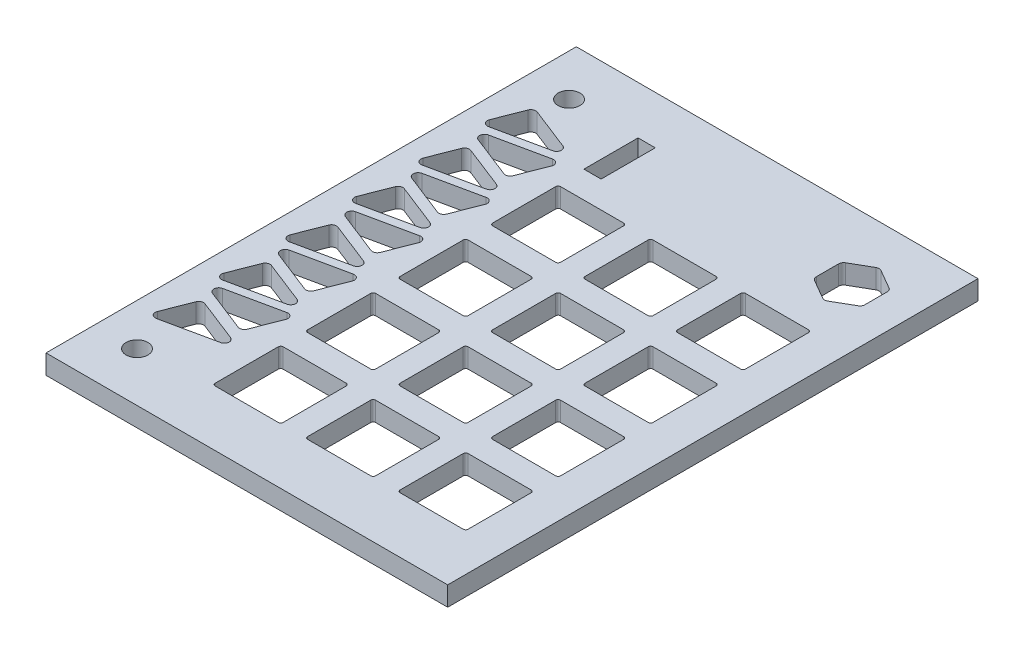
SolidWorks part; units mm, degrees
material "ABS"
ref_plane "Piano frontale" through (0, 0, 0) normal (0, 0, 1) x (1, 0, 0)
ref_plane "Piano superiore" through (0, 0, 0) normal (0, 1, 0) x (1, 0, 0)
ref_plane "Piano destro" through (0, 0, 0) normal (1, 0, 0) x (0, 0, -1)
sketch "Schizzo1" plane through (0, 0, 0) normal (0, 1, 0) x (1, 0, 0)
  line L0 (-41.375, 54.625) -> (41.375, -54.625) construction
  line L1 (-41.375, 54.625) -> (41.375, 54.625)
  line L2 (-41.375, 54.625) -> (-41.375, -54.625)
  line L3 (-41.375, -54.625) -> (41.375, -54.625)
  line L4 (41.375, 54.625) -> (41.375, -54.625)
  line L5 (41.375, 54.625) -> (-41.375, -54.625) construction
  line L6 (-32.75, -44.5) -> (-32.75, 44.5) construction
  line L7 (-32.75, 0) -> (0, 0) construction
  circle A0 centre (-32.75, 44.5) radius 2.25
  circle A1 centre (-32.75, -44.5) radius 2.25
  point P4 (0, 0)
  dimension "D3" = 4.5
  dimension "D1" = 82.75
  dimension "D2" = 109.25
  dimension "D4" = 89
  dimension "D5" = 8.625
extrude "Estrusione-Estrusione1" add sketch "Schizzo1" along normal blind 4
sketch "Schizzo2" plane through (0, 4, 0) normal (0, 1, 0) x (1, 0, 0)
  line L0 (41.375, -54.625) -> (41.375, 54.625) construction
  line L1 (-41.375, -54.625) -> (41.375, -54.625) construction
  line B0 (36.075, -45.625) -> (36.075, 30.575)
  line B1 (-21.075, -45.625) -> (36.075, -45.625)
  line B2 (-18.05, 28.05) -> (-5.05, 28.05)
  line B3 (-18.05, 14.05) -> (-5.05, 14.05)
  line B4 (-18.55, 27.55) -> (-18.55, 14.55)
  line B5 (-4.55, 27.55) -> (-4.55, 14.55)
  line B6 (1, 28.05) -> (14, 28.05)
  line B7 (1, 14.05) -> (14, 14.05)
  line B8 (0.5, 27.55) -> (0.5, 14.55)
  line B9 (14.5, 27.55) -> (14.5, 14.55)
  line B10 (20.05, 28.05) -> (33.05, 28.05)
  line B11 (20.05, 14.05) -> (33.05, 14.05)
  line B12 (19.55, 27.55) -> (19.55, 14.55)
  line B13 (33.55, 27.55) -> (33.55, 14.55)
  line B14 (-18.05, 9) -> (-5.05, 9)
  line B15 (-18.05, -5) -> (-5.05, -5)
  line B16 (-18.55, 8.5) -> (-18.55, -4.5)
  line B17 (-4.55, 8.5) -> (-4.55, -4.5)
  line B18 (1, 9) -> (14, 9)
  line B19 (1, -5) -> (14, -5)
  line B20 (0.5, 8.5) -> (0.5, -4.5)
  line B21 (14.5, 8.5) -> (14.5, -4.5)
  line B22 (20.05, 9) -> (33.05, 9)
  line B23 (20.05, -5) -> (33.05, -5)
  line B24 (19.55, 8.5) -> (19.55, -4.5)
  line B25 (33.55, 8.5) -> (33.55, -4.5)
  line B26 (-18.05, -10.05) -> (-5.05, -10.05)
  line B27 (-18.05, -24.05) -> (-5.05, -24.05)
  line B28 (-18.55, -10.55) -> (-18.55, -23.55)
  line B29 (-4.55, -10.55) -> (-4.55, -23.55)
  line B30 (1, -10.05) -> (14, -10.05)
  line B31 (1, -24.05) -> (14, -24.05)
  line B32 (0.5, -10.55) -> (0.5, -23.55)
  line B33 (14.5, -10.55) -> (14.5, -23.55)
  line B34 (20.05, -10.05) -> (33.05, -10.05)
  line B35 (20.05, -24.05) -> (33.05, -24.05)
  line B36 (19.55, -10.55) -> (19.55, -23.55)
  line B37 (33.55, -10.55) -> (33.55, -23.55)
  line B38 (-18.05, -29.1) -> (-5.05, -29.1)
  line B39 (-18.05, -43.1) -> (-5.05, -43.1)
  line B40 (-18.55, -29.6) -> (-18.55, -42.6)
  line B41 (-4.55, -29.6) -> (-4.55, -42.6)
  line B42 (1, -29.1) -> (14, -29.1)
  line B43 (1, -43.1) -> (14, -43.1)
  line B44 (0.5, -29.6) -> (0.5, -42.6)
  line B45 (14.5, -29.6) -> (14.5, -42.6)
  line B46 (20.05, -29.1) -> (33.05, -29.1)
  line B47 (20.05, -43.1) -> (33.05, -43.1)
  line B48 (19.55, -29.6) -> (19.55, -42.6)
  line B49 (33.55, -29.6) -> (33.55, -42.6)
  line B50 (-21.075, 30.575) -> (36.075, 30.575)
  line B51 (-21.075, -45.625) -> (-21.075, 30.575)
  arc B52 (-18.05, 28.05) -> (-18.55, 27.55) centre (-18.05, 27.55) ccw
  arc B53 (-4.55, 27.55) -> (-5.05, 28.05) centre (-5.05, 27.55) ccw
  arc B54 (-18.55, 14.55) -> (-18.05, 14.05) centre (-18.05, 14.55) ccw
  arc B55 (-5.05, 14.05) -> (-4.55, 14.55) centre (-5.05, 14.55) ccw
  arc B56 (1, 28.05) -> (0.5, 27.55) centre (1, 27.55) ccw
  arc B57 (14.5, 27.55) -> (14, 28.05) centre (14, 27.55) ccw
  arc B58 (0.5, 14.55) -> (1, 14.05) centre (1, 14.55) ccw
  arc B59 (14, 14.05) -> (14.5, 14.55) centre (14, 14.55) ccw
  arc B60 (20.05, 28.05) -> (19.55, 27.55) centre (20.05, 27.55) ccw
  arc B61 (33.55, 27.55) -> (33.05, 28.05) centre (33.05, 27.55) ccw
  arc B62 (19.55, 14.55) -> (20.05, 14.05) centre (20.05, 14.55) ccw
  arc B63 (33.05, 14.05) -> (33.55, 14.55) centre (33.05, 14.55) ccw
  arc B64 (-18.05, 9) -> (-18.55, 8.5) centre (-18.05, 8.5) ccw
  arc B65 (-4.55, 8.5) -> (-5.05, 9) centre (-5.05, 8.5) ccw
  arc B66 (-18.55, -4.5) -> (-18.05, -5) centre (-18.05, -4.5) ccw
  arc B67 (-5.05, -5) -> (-4.55, -4.5) centre (-5.05, -4.5) ccw
  arc B68 (1, 9) -> (0.5, 8.5) centre (1, 8.5) ccw
  arc B69 (14.5, 8.5) -> (14, 9) centre (14, 8.5) ccw
  arc B70 (0.5, -4.5) -> (1, -5) centre (1, -4.5) ccw
  arc B71 (14, -5) -> (14.5, -4.5) centre (14, -4.5) ccw
  arc B72 (20.05, 9) -> (19.55, 8.5) centre (20.05, 8.5) ccw
  arc B73 (33.55, 8.5) -> (33.05, 9) centre (33.05, 8.5) ccw
  arc B74 (19.55, -4.5) -> (20.05, -5) centre (20.05, -4.5) ccw
  arc B75 (33.05, -5) -> (33.55, -4.5) centre (33.05, -4.5) ccw
  arc B76 (-18.05, -10.05) -> (-18.55, -10.55) centre (-18.05, -10.55) ccw
  arc B77 (-4.55, -10.55) -> (-5.05, -10.05) centre (-5.05, -10.55) ccw
  arc B78 (-18.55, -23.55) -> (-18.05, -24.05) centre (-18.05, -23.55) ccw
  arc B79 (-5.05, -24.05) -> (-4.55, -23.55) centre (-5.05, -23.55) ccw
  arc B80 (1, -10.05) -> (0.5, -10.55) centre (1, -10.55) ccw
  arc B81 (14.5, -10.55) -> (14, -10.05) centre (14, -10.55) ccw
  arc B82 (0.5, -23.55) -> (1, -24.05) centre (1, -23.55) ccw
  arc B83 (14, -24.05) -> (14.5, -23.55) centre (14, -23.55) ccw
  arc B84 (20.05, -10.05) -> (19.55, -10.55) centre (20.05, -10.55) ccw
  arc B85 (33.55, -10.55) -> (33.05, -10.05) centre (33.05, -10.55) ccw
  arc B86 (19.55, -23.55) -> (20.05, -24.05) centre (20.05, -23.55) ccw
  arc B87 (33.05, -24.05) -> (33.55, -23.55) centre (33.05, -23.55) ccw
  arc B88 (-18.05, -29.1) -> (-18.55, -29.6) centre (-18.05, -29.6) ccw
  arc B89 (-4.55, -29.6) -> (-5.05, -29.1) centre (-5.05, -29.6) ccw
  arc B90 (-18.55, -42.6) -> (-18.05, -43.1) centre (-18.05, -42.6) ccw
  arc B91 (-5.05, -43.1) -> (-4.55, -42.6) centre (-5.05, -42.6) ccw
  arc B92 (1, -29.1) -> (0.5, -29.6) centre (1, -29.6) ccw
  arc B93 (14.5, -29.6) -> (14, -29.1) centre (14, -29.6) ccw
  arc B94 (0.5, -42.6) -> (1, -43.1) centre (1, -42.6) ccw
  arc B95 (14, -43.1) -> (14.5, -42.6) centre (14, -42.6) ccw
  arc B96 (20.05, -29.1) -> (19.55, -29.6) centre (20.05, -29.6) ccw
  arc B97 (33.55, -29.6) -> (33.05, -29.1) centre (33.05, -29.6) ccw
  arc B98 (19.55, -42.6) -> (20.05, -43.1) centre (20.05, -42.6) ccw
  arc B99 (33.05, -43.1) -> (33.55, -42.6) centre (33.05, -42.6) ccw
  dimension "D1" = 5.3
  dimension "D2" = 9
sketch_block_instance "plate-2026-08-13T19_05_16.025Z-1"
sketch_block "plate-2026-08-13T19_05_16.025Z"
extrude "Taglio-Estrusione1" cut sketch "Schizzo2" against normal blind 19 contours B3 B55 B5 B53 B2 B52 B4 B54 | B7 B59 B9 B57 B6 B56 B8 B58 | B11 B63 B13 B61 B10 B60 B12 B62 | B23 B75 B25 B73 B22 B72 B24 B74 | B15 B67 B17 B65 B14 B64 B16 B66 | B19 B71 B21 B69 B18 B68 B20 B70 | B27 B79 B29 B77 B26 B76 B28 B78 | B31 B83 B33 B81 B30 B80 B32 B82 | B35 B87 B37 B85 B34 B84 B36 B86 | B47 B99 B49 B97 B46 B96 B48 B98 | B43 B95 B45 B93 B42 B92 B44 B94 | B39 B91 B41 B89 B38 B88 B40 B90
sketch "Schizzo3" plane through (0, 4, 0) normal (0, 1, 0) x (1, 0, 0)
  line L0 (41.375, 54.625) -> (-41.375, 54.625) construction
  line L1 (-18.7525, 44.7275) -> (-15.2125, 44.7275)
  line L2 (-18.7525, 44.7275) -> (-18.7525, 33.5675)
  line L3 (-18.7525, 33.5675) -> (-15.2125, 33.5675)
  line L4 (-15.2125, 44.7275) -> (-15.2125, 33.5675)
  line L5 (-41.375, 54.625) -> (-41.375, -54.625) construction
  dimension "D1" = 3.54
  dimension "D2" = 11.16
  dimension "D3" = 9.8975
  dimension "D4" = 22.6225
extrude "Taglio-Estrusione2" cut sketch "Schizzo3" against normal blind 19
sketch "Schizzo4" plane through (0, 4, 0) normal (0, 1, 0) x (1, 0, 0)
  line L0 (-35.0584, -16.3626) -> (-37.2982, -22.0833)
  line L1 (-21.975, -37.5) -> (-37.975, -37.5) construction
  line L2 (-21.975, -37.5) -> (-21.975, 39.4371) construction
  line L3 (-21.975, 39.4371) -> (-37.975, 39.4371) construction
  line L4 (-37.975, -37.5) -> (-37.975, 39.4371) construction
  line L5 (-41.375, 54.625) -> (-41.375, -54.625) construction
  line L6 (-36.1591, -37.114) -> (-25.2373, -34.7925)
  line L7 (-25.0806, -32.8832) -> (-33.7627, -29.484)
  line L8 (-35.0584, -30.0506) -> (-37.2982, -35.7713)
  line L9 (-34.8694, -26.8353) -> (-26.1873, -30.2345)
  line L10 (-24.8916, -29.6679) -> (-22.6518, -23.9472)
  line L11 (-23.7909, -22.6045) -> (-34.7127, -24.926)
  line L12 (-36.1591, -23.426) -> (-25.2373, -21.1045)
  line L13 (-25.0806, -19.1952) -> (-33.7627, -15.796)
  line L14 (-23.7909, -8.9165) -> (-34.7127, -11.238)
  line L15 (-34.8694, -13.1473) -> (-26.1873, -16.5465)
  line L16 (-24.8916, -15.9799) -> (-22.6518, -10.2592)
  line L17 (-35.0584, -2.6746) -> (-37.2982, -8.3953)
  line L18 (-36.1591, -9.738) -> (-25.2373, -7.4165)
  line L19 (-25.0806, -5.5072) -> (-33.7627, -2.108)
  line L20 (-23.7909, 4.7715) -> (-34.7127, 2.45)
  line L21 (-34.8694, 0.5407) -> (-26.1873, -2.8585)
  line L22 (-24.8916, -2.2919) -> (-22.6518, 3.4288)
  line L23 (-35.0584, 11.0134) -> (-37.2982, 5.2927)
  line L24 (-36.1591, 3.95) -> (-25.2373, 6.2715)
  line L25 (-25.0806, 8.1808) -> (-33.7627, 11.58)
  line L26 (-23.7909, 18.4595) -> (-34.7127, 16.138)
  line L27 (-34.8694, 14.2287) -> (-26.1873, 10.8295)
  line L28 (-24.8916, 11.3961) -> (-22.6518, 17.1168)
  line L29 (-35.0584, 24.7014) -> (-37.2982, 18.9807)
  line L30 (-36.1591, 17.638) -> (-25.2373, 19.9595)
  line L31 (-25.0806, 21.8688) -> (-33.7627, 25.268)
  line L32 (-23.7909, 32.1475) -> (-34.7127, 29.826)
  line L33 (-34.8694, 27.9167) -> (-26.1873, 24.5175)
  line L34 (-24.8916, 25.0841) -> (-22.6518, 30.8048)
  line L35 (-35.0584, 38.3894) -> (-37.2982, 32.6687)
  line L36 (-36.1591, 31.326) -> (-25.2373, 33.6475)
  line L37 (-25.0806, 35.5569) -> (-33.7627, 38.956)
  line L41 (-23.7909, 45.8355) -> (-34.7127, 43.514) [skipped]
  line L42 (-34.8694, 41.6047) -> (-26.1873, 38.2055) [skipped]
  line L43 (-24.8916, 38.7721) -> (-22.6518, 44.4928) [skipped]
  line L44 (29.375, 34.8515) -> (29.375, 46.3985) construction
  line L45 (28.875, 46.1098) -> (24.875, 43.8004)
  line L46 (24.375, 42.9344) -> (24.375, 38.3156)
  line L47 (24.875, 37.4496) -> (28.875, 35.1402)
  line L48 (29.875, 35.1402) -> (33.875, 37.4496)
  line L49 (34.375, 38.3156) -> (34.375, 42.9344)
  line L50 (33.875, 43.8004) -> (29.875, 46.1098)
  line L51 (41.375, -54.625) -> (41.375, 54.625) construction
  line L52 (41.375, 54.625) -> (-41.375, 54.625) construction
  circle A0 centre (-32.75, -44.5) radius 2.25 construction
  arc A1 (-22.6518, -23.9472) -> (-23.7909, -22.6045) centre (-23.583, -23.5827) ccw
  arc A2 (-26.1873, -30.2345) -> (-24.8916, -29.6679) centre (-25.8228, -29.3033) ccw
  arc A3 (-34.7127, -24.926) -> (-34.8694, -26.8353) centre (-34.5048, -25.9042) ccw
  arc A4 (-25.2373, -34.7925) -> (-25.0806, -32.8832) centre (-25.4452, -33.8144) ccw
  arc A5 (-33.7627, -29.484) -> (-35.0584, -30.0506) centre (-34.1272, -30.4152) ccw
  arc A6 (-36.1591, -37.114) -> (-37.2982, -35.7713) centre (-36.367, -36.1359) cw
  arc A7 (-36.1591, -23.426) -> (-37.2982, -22.0833) centre (-36.367, -22.4479) cw
  arc A8 (-33.7627, -15.796) -> (-35.0584, -16.3626) centre (-34.1272, -16.7272) ccw
  arc A9 (-25.2373, -21.1045) -> (-25.0806, -19.1952) centre (-25.4452, -20.1264) ccw
  arc A10 (-34.7127, -11.238) -> (-34.8694, -13.1473) centre (-34.5048, -12.2161) ccw
  arc A11 (-22.6518, -10.2592) -> (-23.7909, -8.9165) centre (-23.583, -9.8946) ccw
  arc A12 (-26.1873, -16.5465) -> (-24.8916, -15.9799) centre (-25.8228, -15.6153) ccw
  arc A13 (-36.1591, -9.738) -> (-37.2982, -8.3953) centre (-36.367, -8.7599) cw
  arc A14 (-33.7627, -2.108) -> (-35.0584, -2.6746) centre (-34.1272, -3.0392) ccw
  arc A15 (-25.2373, -7.4165) -> (-25.0806, -5.5072) centre (-25.4452, -6.4383) ccw
  arc A16 (-34.7127, 2.45) -> (-34.8694, 0.5407) centre (-34.5048, 1.4719) ccw
  arc A17 (-22.6518, 3.4288) -> (-23.7909, 4.7715) centre (-23.583, 3.7934) ccw
  arc A18 (-26.1873, -2.8585) -> (-24.8916, -2.2919) centre (-25.8228, -1.9273) ccw
  arc A19 (-36.1591, 3.95) -> (-37.2982, 5.2927) centre (-36.367, 4.9282) cw
  arc A20 (-33.7627, 11.58) -> (-35.0584, 11.0134) centre (-34.1272, 10.6489) ccw
  arc A21 (-25.2373, 6.2715) -> (-25.0806, 8.1808) centre (-25.4452, 7.2497) ccw
  arc A22 (-34.7127, 16.138) -> (-34.8694, 14.2287) centre (-34.5048, 15.1599) ccw
  arc A23 (-22.6518, 17.1168) -> (-23.7909, 18.4595) centre (-23.583, 17.4814) ccw
  arc A24 (-26.1873, 10.8295) -> (-24.8916, 11.3961) centre (-25.8228, 11.7607) ccw
  arc A25 (-36.1591, 17.638) -> (-37.2982, 18.9807) centre (-36.367, 18.6162) cw
  arc A26 (-33.7627, 25.268) -> (-35.0584, 24.7014) centre (-34.1272, 24.3369) ccw
  arc A27 (-25.2373, 19.9595) -> (-25.0806, 21.8688) centre (-25.4452, 20.9377) ccw
  arc A28 (-34.7127, 29.826) -> (-34.8694, 27.9167) centre (-34.5048, 28.8479) ccw
  arc A29 (-22.6518, 30.8048) -> (-23.7909, 32.1475) centre (-23.583, 31.1694) ccw
  arc A30 (-26.1873, 24.5175) -> (-24.8916, 25.0841) centre (-25.8228, 25.4487) ccw
  arc A31 (-36.1591, 31.326) -> (-37.2982, 32.6687) centre (-36.367, 32.3042) cw
  arc A32 (-33.7627, 38.956) -> (-35.0584, 38.3894) centre (-34.1272, 38.0249) ccw
  arc A33 (-25.2373, 33.6475) -> (-25.0806, 35.5569) centre (-25.4452, 34.6257) ccw
  arc A37 (-34.7127, 43.514) -> (-34.8694, 41.6047) centre (-34.5048, 42.5359) ccw [skipped]
  arc A38 (-26.1873, 38.2055) -> (-24.8916, 38.7721) centre (-25.8228, 39.1367) ccw [skipped]
  arc A39 (-22.6518, 44.4928) -> (-23.7909, 45.8355) centre (-23.583, 44.8574) ccw [skipped]
  circle A40 centre (29.375, 40.625) radius 5 construction
  arc A41 (24.875, 37.4496) -> (24.375, 38.3156) centre (25.375, 38.3156) cw
  arc A42 (24.375, 42.9344) -> (24.875, 43.8004) centre (25.375, 42.9344) cw
  arc A43 (29.875, 46.1098) -> (28.875, 46.1098) centre (29.375, 45.2438) ccw
  arc A44 (34.375, 42.9344) -> (33.875, 43.8004) centre (33.375, 42.9344) ccw
  arc A45 (33.875, 37.4496) -> (34.375, 38.3156) centre (33.375, 38.3156) ccw
  arc A46 (29.875, 35.1402) -> (28.875, 35.1402) centre (29.375, 36.0062) cw
  point P16 (-21.975, -22.2185)
  point P19 (-25.2562, -30.5991)
  point P22 (-37.975, -25.6194)
  point P25 (-21.975, -34.0991)
  point P28 (-34.6938, -29.1194)
  point P31 (-37.975, -37.5)
  point P138 (31.375, 38.7869)
  dimension "D7" = 1
  dimension "D10" = 10
  dimension "D11" = 12
  dimension "D13" = 1
  dimension "D1" = 16
  dimension "D2" = 3.4
  dimension "D3" = 3.5
  dimension "D4" = 7
  dimension "D5" = 12
  dimension "D6" = 9
  dimension "D9" = 1.5
  dimension "D12" = 14
  dimension "D8" = 6
extrude "Taglio-Estrusione3" cut sketch "Schizzo4" against normal blind 19
